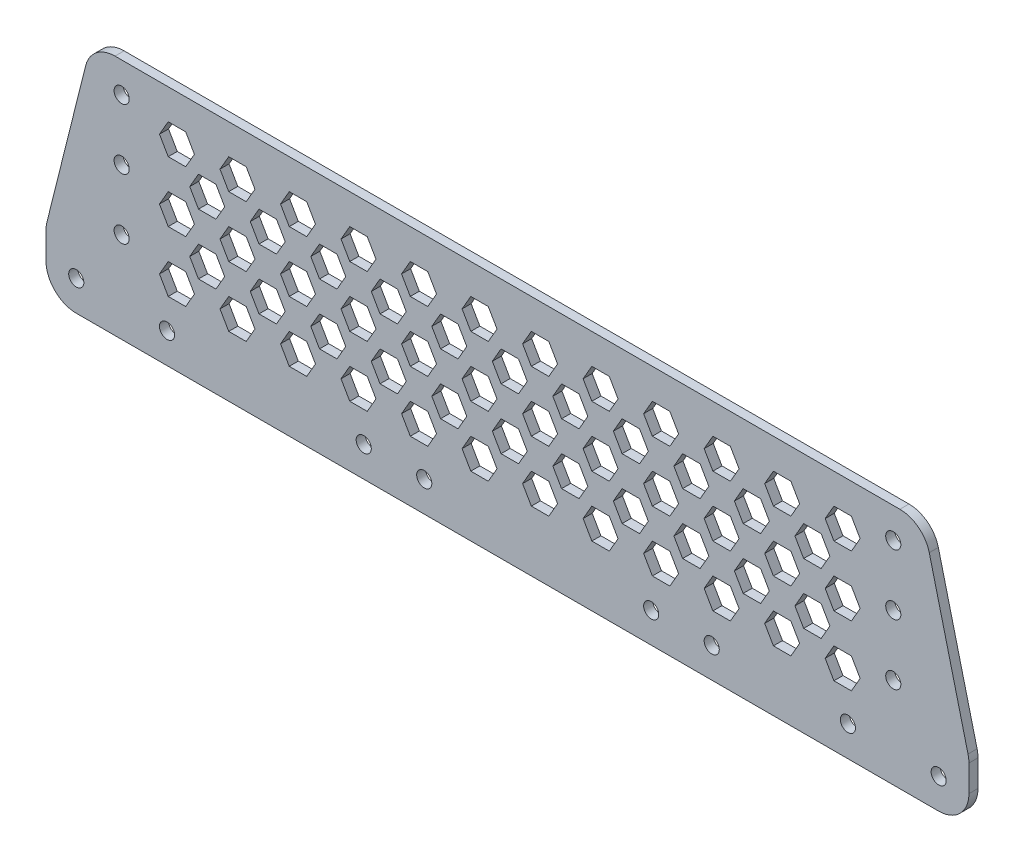
SolidWorks part; units mm, degrees
material "Thornel Mat VMA"
ref_plane "前视基准面" through (0, 0, 0) normal (0, 0, 1) x (1, 0, 0)
ref_plane "上视基准面" through (0, 0, 0) normal (0, 1, 0) x (1, 0, 0)
ref_plane "右视基准面" through (0, 0, 0) normal (1, 0, 0) x (0, 0, -1)
sketch "Sketch1" plane through (0, 0, 0) normal (0, 0, 1) x (1, 0, 0)
  line L0 (0, 0) -> (-15, 0)
  line L1 (0, 0) -> (275, 0)
  line L2 (0, 0) -> (0, 80) construction
  line L3 (0, 80) -> (275, 80)
  line L4 (275, 0) -> (275, 80) construction
  line L5 (-140, 0) -> (340, 0) construction
  line L6 (-15, 0) -> (-15, 20)
  line L7 (-140, 20) -> (340, 20) construction
  line L8 (-15, 20) -> (0, 80)
  line L9 (275, 0) -> (290, 0)
  line L10 (290, 0) -> (290, 20)
  line L11 (290, 20) -> (275, 80)
  dimension "D1" = 80
  dimension "D2" = 275
  dimension "D3" = 15
  dimension "D4" = 15
extrude "Boss-Extrude1" add sketch "Sketch1" along normal blind 3
sketch "Sketch3" plane through (0, 0, 3) normal (0, 0, 1) x (1, 0, 0)
  line L0 (275, 80) -> (0, 80) construction
  line L1 (34.047, 65) -> (31.1603, 70)
  line L2 (31.1603, 70) -> (25.3868, 70)
  line L3 (25.3868, 70) -> (22.5, 65)
  line L4 (22.5, 65) -> (25.3868, 60)
  line L5 (25.3868, 60) -> (31.1603, 60)
  line L6 (31.1603, 60) -> (34.047, 65)
  circle A0 centre (28.2735, 65) radius 5 construction
  point P14 (0, 0)
  dimension "D1" = 10
  dimension "D2" = 10
  dimension "D3" = 22.5
extrude "Cut-Extrude2" cut sketch "Sketch3" against normal blind 3
pattern_linear "LPattern1" count 12 spacing 20 along (1, 0, 0) of "Cut-Extrude2"
sketch "Sketch5" plane through (0, 0, 3) normal (0, 0, 1) x (1, 0, 0)
  line L0 (22.5, 65) -> (54.047, 65) construction
  line L2 (32.5, 55) -> (35.3868, 50)
  line L3 (35.3868, 50) -> (41.1603, 50)
  line L4 (41.1603, 50) -> (44.047, 55)
  line L5 (44.047, 55) -> (41.1603, 60)
  line L6 (41.1603, 60) -> (35.3868, 60)
  line L7 (35.3868, 60) -> (32.5, 55)
  line L8 (51.1603, 70) -> (45.3868, 70) construction
  circle A0 centre (38.2735, 55) radius 5 construction
  point P5 (48.2735, 70)
  dimension "D1" = 10
  dimension "D2" = 10
  dimension "D3" = 10
extrude "Cut-Extrude3" cut sketch "Sketch5" against normal blind 3
pattern_linear "LPattern2" count 11 spacing 20 along (1, 0, 0) of "Cut-Extrude3"
sketch "Sketch6" plane through (0, 0, 3) normal (0, 0, 1) x (1, 0, 0)
  line L0 (28.2735, 70) -> (28.2735, 4.7416) construction
  line L1 (31.1603, 70) -> (25.3868, 70) construction
  line L2 (35.3868, 50) -> (41.1603, 50) construction
  line L3 (34.047, 45) -> (31.1603, 50)
  line L4 (31.1603, 50) -> (25.3868, 50)
  line L5 (25.3868, 50) -> (22.5, 45)
  line L6 (22.5, 45) -> (25.3868, 40)
  line L7 (25.3868, 40) -> (31.1603, 40)
  line L8 (31.1603, 40) -> (34.047, 45)
  circle A0 centre (28.2735, 45) radius 5 construction
  dimension "D1" = 10
  dimension "D2" = 5
extrude "Cut-Extrude4" cut sketch "Sketch6" against normal blind 3
pattern_linear "LPattern3" count 12 spacing 20 along (1, 0, 0) of "Cut-Extrude4"
pattern_linear "LPattern4" count 2 spacing 20 along (0, -1, 0) of "Cut-Extrude3", "Cut-Extrude4", "LPattern3", "LPattern2"
sketch "Sketch7" plane through (0, 0, 0) normal (0, 0, -1) x (-1, 0, 0)
  line L0 (-137.5, 80) -> (-137.5, 0) construction
  line L1 (-275, 80) -> (0, 80) construction
  line L2 (15, 0) -> (-290, 0) construction
  line L3 (-10, 80) -> (-10, 0) construction
  line L4 (-265, 80) -> (-265, 0) construction
  line L5 (-265, 10) -> (-10, 10) construction
  circle A0 centre (-10, 70) radius 2.5
  circle A1 centre (-10, 50) radius 2.5
  circle A3 centre (-10, 30) radius 2.5
  circle A4 centre (-265, 30) radius 2.5
  circle A5 centre (-265, 50) radius 2.5
  circle A6 centre (-265, 70) radius 2.5
  circle A7 centre (-110, 10) radius 2.5
  circle A8 centre (-25, 10) radius 2.5
  circle A9 centre (-250, 10) radius 2.5
  circle A10 centre (-90, 10) radius 2.5
  circle A11 centre (-185, 10) radius 2.5
  circle A12 centre (-205, 10) radius 2.5
  circle A14 centre (-280, 10) radius 2.5
  circle A15 centre (5, 10) radius 2.5
  point P40 (-290, 0)
  dimension "D3" = 5
  dimension "D2" = 5
  dimension "D4" = 5
  dimension "D9" = 5
  dimension "D11" = 5
  dimension "D12" = 180
  dimension "D13" = 5
  dimension "D17" = 5
  dimension "D18" = 5
  dimension "D1" = 127.5
  dimension "D5" = 30
  dimension "D6" = 20
  dimension "D7" = 20
  dimension "D8" = 10
  dimension "D10" = 15
  dimension "D14" = 20
  dimension "D15" = 45
  dimension "D16" = 20
extrude "Cut-Extrude5" cut sketch "Sketch7" against normal blind 3
fillet "Fillet1" radius 10 6 edges at (290, 0, 1.5) (290, 20, 1.5) (275, 80, 1.5) (-15, 0, 1.5) (-15, 20, 1.5) (0, 80, 1.5)
